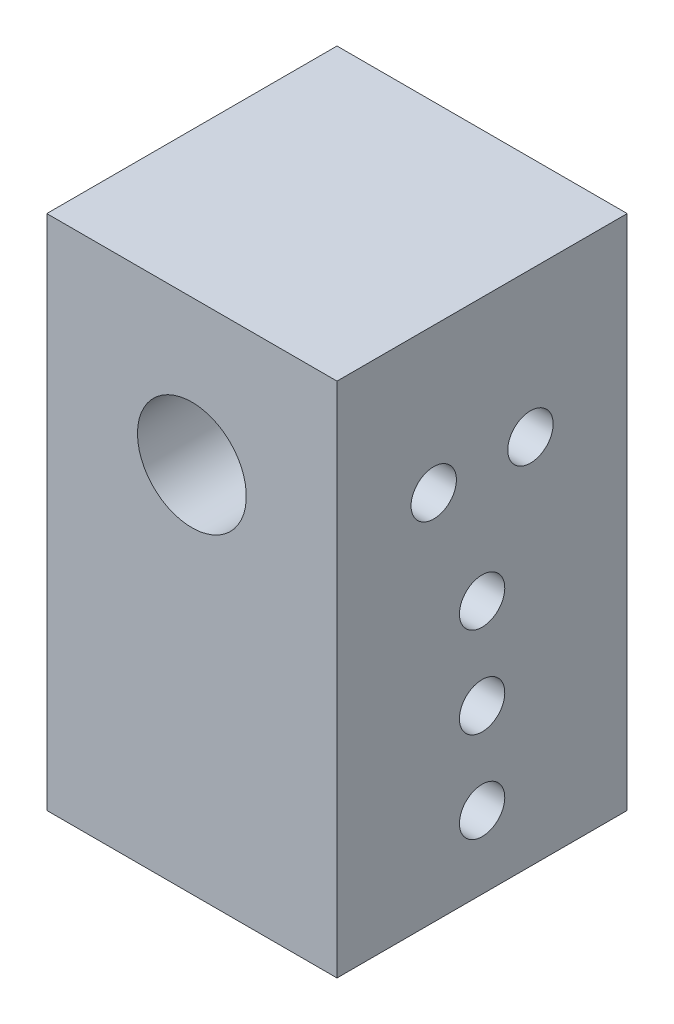
SolidWorks part; units mm, degrees
material "6061-T6 (SS)"
ref_plane "Frontal Plane" through (0, 0, 0) normal (0, 0, 1) x (1, 0, 0)
ref_plane "Horizontal Plane" through (0, 0, 0) normal (0, 1, 0) x (1, 0, 0)
ref_plane "Profile Plane" through (0, 0, 0) normal (1, 0, 0) x (0, 0, -1)
sketch "Sketch1" plane through (0, 0, 0) normal (0, 0, 1) x (1, 0, 0)
  line L0 (-8, 0) -> (8, 0)
  line L1 (8, 0) -> (8, 28.5)
  line L2 (8, 28.5) -> (-8, 28.5)
  line L3 (-8, 28.5) -> (-8, 0)
  point P4 (0, 0)
  dimension "D1" = 28.5
  dimension "D2" = 16
extrude "Boss-Extrude1" add sketch "Sketch1" along normal blind 16
ref_plane "Plane1" through (0, 0, 0) normal (0, -1, 0) x (-1, 0, 0)
sketch "Sketch2" plane through (0, 0, 0) normal (0, -1, 0) x (-1, 0, 0)
  line L0 (-8, -16) -> (-8, 0) construction
  circle A0 centre (0, -8) radius 5
  point P5 (-8, -8)
  dimension "D1" = 10
extrude "Cut-Extrude1" cut sketch "Sketch2" against normal blind 16
ref_plane "Plane2" through (0, 0, 0) normal (0, 0, -1) x (-1, 0, 0)
sketch "Sketch3" plane through (0, 0, 0) normal (0, 0, -1) x (-1, 0, 0)
  line L0 (-8, 28.5) -> (8, 28.5) construction
  circle A0 centre (0, 20.5) radius 3
  dimension "D1" = 6
  dimension "D2" = 8
extrude "Cut-Extrude2" cut sketch "Sketch3" against normal through all
sketch "Sketch4" plane through (8, 0, 0) normal (1, 0, 0) x (0, 0, -1)
  line L0 (-16, 28.5) -> (0, 28.5) construction
  line L1 (-16, 0) -> (-16, 28.5) construction
  line L3 (0, 0) -> (0, 28.5) construction
  circle A0 centre (-10.6667, 20.5) radius 1.25
  circle A1 centre (-5.3333, 20.5) radius 1.25
  dimension "D2" = 2.5
  dimension "D1" = 8
  dimension "D3" = 5.3333
  dimension "D4" = 5.3333
extrude "Cut-Extrude3" cut sketch "Sketch4" against normal blind 10
thread "Thread1" pitch 0.5 start angle 0, offset 0, length 8, pitch 0.5, diameter 2.5
ref_plane "Plane3" through (8, 20.5, 11.9167) normal (0, -1, 0) x (0, 0, 1)
sketch "Thread Profile1" plane through (8, 20.5, 11.9167) normal (0, -1, 0) x (0, 0, 1)
  line L0 (0, 0) -> (0, 0.5) construction
  line L1 (0, 0) -> (0.2706, 0.1562)
  line L2 (0.2706, 0.1562) -> (0.2706, 0.2187)
  line L3 (0.2706, 0.2187) -> (0, 0.375)
  line L4 (0.2706, 0.1875) -> (0, 0.1875) construction
  line L11 (0, 0) -> (0, 0.375)
  point P2 (0, 0)
  dimension "Pitch" = 0.5
  dimension "Profile_Angle" = 60
  dimension "Profile_Land" = 0.0625
  dimension "Profile_Height" = 0.2706
thread "Thread2" pitch 0.5 start angle 0, offset 0, length 8, pitch 0.5, diameter 2.5
ref_plane "Plane4" through (8, 20.5, 6.5833) normal (0, -1, 0) x (0, 0, 1)
sketch "Thread Profile2" plane through (8, 20.5, 6.5833) normal (0, -1, 0) x (0, 0, 1)
  line L0 (0, 0) -> (0, 0.5) construction
  line L1 (0, 0) -> (0.2706, 0.1562)
  line L2 (0.2706, 0.1562) -> (0.2706, 0.2187)
  line L3 (0.2706, 0.2187) -> (0, 0.375)
  line L4 (0.2706, 0.1875) -> (0, 0.1875) construction
  line L11 (0, 0) -> (0, 0.375)
  point P2 (0, 0)
  dimension "Pitch" = 0.5
  dimension "Profile_Angle" = 60
  dimension "Profile_Land" = 0.0625
  dimension "Profile_Height" = 0.2706
sketch "Sketch6" plane through (8, 0, 0) normal (1, 0, 0) x (0, 0, -1)
  line L0 (-16, 28.5) -> (0, 28.5) construction
  circle A0 centre (-8, 14) radius 1.25
  circle A1 centre (-8, 9) radius 1.25
  circle A2 centre (-8, 4) radius 1.25
  point P9 (-8, 28.5)
  dimension "D3" = 2.5
  dimension "D1" = 5
  dimension "D2" = 5
  dimension "D4" = 4
extrude "Cut-Extrude4" cut sketch "Sketch6" against normal blind 8
thread "Thread3" pitch 0.5 start angle 0, offset 0, length 8, pitch 0.5, diameter 2.5
ref_plane "Plane5" through (8, 14, 9.25) normal (0, -1, 0) x (0, 0, 1)
sketch "Thread Profile3" plane through (8, 14, 9.25) normal (0, -1, 0) x (0, 0, 1)
  line L0 (0, 0) -> (0, 0.5) construction
  line L1 (0, 0) -> (0.2706, 0.1562)
  line L2 (0.2706, 0.1562) -> (0.2706, 0.2187)
  line L3 (0.2706, 0.2187) -> (0, 0.375)
  line L4 (0.2706, 0.1875) -> (0, 0.1875) construction
  line L11 (0, 0) -> (0, 0.375)
  point P2 (0, 0)
  dimension "Pitch" = 0.5
  dimension "Profile_Angle" = 60
  dimension "Profile_Land" = 0.0625
  dimension "Profile_Height" = 0.2706
thread "Thread4" pitch 0.5 start angle 0, offset 0, length 8, pitch 0.5, diameter 2.5
ref_plane "Plane6" through (8, 9, 9.25) normal (0, -1, 0) x (0, 0, 1)
sketch "Thread Profile4" plane through (8, 9, 9.25) normal (0, -1, 0) x (0, 0, 1)
  line L0 (0, 0) -> (0, 0.5) construction
  line L1 (0, 0) -> (0.2706, 0.1562)
  line L2 (0.2706, 0.1562) -> (0.2706, 0.2187)
  line L3 (0.2706, 0.2187) -> (0, 0.375)
  line L4 (0.2706, 0.1875) -> (0, 0.1875) construction
  line L11 (0, 0) -> (0, 0.375)
  point P2 (0, 0)
  dimension "Pitch" = 0.5
  dimension "Profile_Angle" = 60
  dimension "Profile_Land" = 0.0625
  dimension "Profile_Height" = 0.2706
thread "Thread5" pitch 0.5 start angle 0, offset 0, length 8, pitch 0.5, diameter 2.5
ref_plane "Plane7" through (8, 4, 9.25) normal (0, -1, 0) x (0, 0, 1)
sketch "Thread Profile5" plane through (8, 4, 9.25) normal (0, -1, 0) x (0, 0, 1)
  line L0 (0, 0) -> (0, 0.5) construction
  line L1 (0, 0) -> (0.2706, 0.1562)
  line L2 (0.2706, 0.1562) -> (0.2706, 0.2187)
  line L3 (0.2706, 0.2187) -> (0, 0.375)
  line L4 (0.2706, 0.1875) -> (0, 0.1875) construction
  line L11 (0, 0) -> (0, 0.375)
  point P2 (0, 0)
  dimension "Pitch" = 0.5
  dimension "Profile_Angle" = 60
  dimension "Profile_Land" = 0.0625
  dimension "Profile_Height" = 0.2706
equation "\"BaseL\"= 6ft"
equation "\"BaseW\"= 5.5in"
equation "\"BaseThickness\"= 1in"
equation "\"RailGap\"= 4cm"
equation "\"SlidePlateL\"= 8cm"
equation "\"SlidePlateW\"= 11cm"
equation "\"SlidePlateThickness\"= 5mm"
equation "\"SlidePlateClearance\"= 1cm"
equation "\"BoxThickness\"= .5cm"
equation "\"BoxX\"= \"RailGap\" + 30mm"
equation "\"BoxH\"= 2cm + \"SlidePlateClearance\" + \"SlidePlateThickness\" + 3cm"
equation "\"PulleyRadius\"= 15.1mm"
equation "\"PulleyH\"= 30mm + 21.4056mm - 2.5mm"
equation "\"PulleyShaftDiameter\"= .3125in"
equation "\"PulleyShaftL\"= 4in"
equation "\"PulleyShaft2L\"= 3in"
equation "\"MotorL\"= 4.43in"
equation "\"MotorRadius\"= 1.291in"
equation "\"MotorShaftRadius\"= .15625in"
equation "\"MotorShaftL\"= 1.75in"
equation "\"HeadstoneThickness\"= 7.5mm"
equation "\"BeltL\"= 1500mm + \"80\""
equation "\"BeltThickness\"= 2.5mm"
equation "\"BeltW\"= .375in"
equation "\"BeltLockH\"= \"PulleyH\" + 19.4056mm - (\"SlidePlateThickness\" + \"SlidePlateClearance\" + 15mm + 5mm)"
equation "\"EncoderL\"= 33mm"
equation "\"EncoderRadius\"= 19mm"
equation "\"EncoderShaftRadius\"= 3mm"
equation "\"EncoderShaftL\"= 15mm"
equation "\"PendulumShaftL\"= \"100mm\" "
equation "\"PendulumShaftRadius\"= 3mm"
equation "\"D1@Sketch1\"=\"PendulumShaftRadius\"*2 + 2.25cm"
equation "\"RodL\"= 39in"
equation "\"RodRadius\"= 3mm"
equation "\"D2@Sketch1\"=\"RodRadius\"*2 + 1cm"
equation "\"D1@Boss-Extrude1\"=\"RodRadius\"*2 + 1cm"
equation "\"D3@Sketch4\"=16/3"
equation "\"D4@Sketch4\"=\"D3@Sketch4\""
